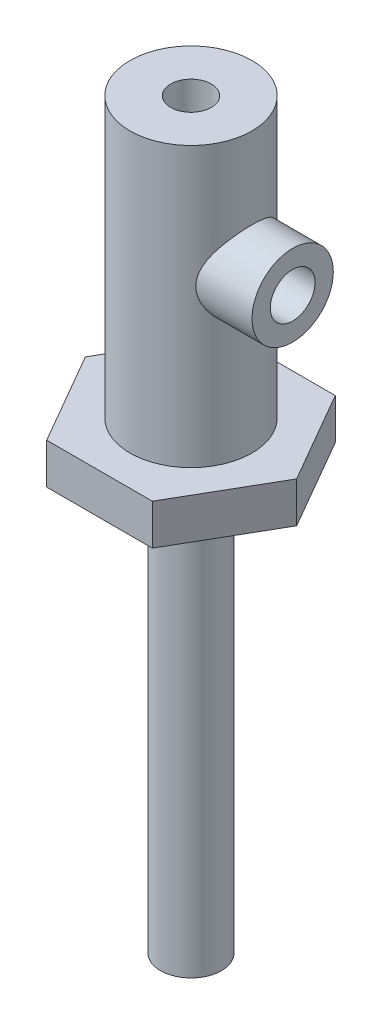
SolidWorks part; units mm, degrees
ref_plane "Front Plane" through (0, 0, 0) normal (0, 0, 1) x (1, 0, 0)
ref_plane "Top Plane" through (0, 0, 0) normal (0, 1, 0) x (1, 0, 0)
ref_plane "Right Plane" through (0, 0, 0) normal (1, 0, 0) x (0, 0, -1)
sketch "Sketch1" plane through (0, 0, 0) normal (0, 1, 0) x (1, 0, 0)
  circle A0 centre (0, 0) radius 3
  dimension "D1" = 6
extrude "Boss-Extrude1" add sketch "Sketch1" along normal blind 15.725
ref_plane "Plane1" through (0, 15.725, 0) normal (0, 1, 0) x (1, 0, 0)
ref_point "Point1"
sketch "Sketch2" plane through (0, 15.725, 0) normal (0, 1, 0) x (1, 0, 0)
  circle A0 centre (0, 0) radius 1
  dimension "D1" = 2
extrude "Cut-Extrude3" cut sketch "Sketch2" against normal blind 10.2
ref_plane "Plane2" through (0, 0, 0) normal (0, -1, 0) x (-1, 0, 0)
sketch "Sketch3" plane through (0, 0, 0) normal (0, -1, 0) x (-1, 0, 0)
  line L1 (5.1962, 0) -> (2.5981, 4.5)
  line L2 (2.5981, 4.5) -> (-2.5981, 4.5)
  line L3 (-2.5981, 4.5) -> (-5.1962, 0)
  line L4 (-5.1962, 0) -> (-2.5981, -4.5)
  line L5 (-2.5981, -4.5) -> (2.5981, -4.5)
  line L6 (2.5981, -4.5) -> (5.1962, 0)
  circle A0 centre (0, 0) radius 4.5 construction
extrude "Boss-Extrude2" add sketch "Sketch3" against normal blind 2
sketch "Sketch4" plane through (0, 0, 0) normal (0, -1, 0) x (-1, 0, 0)
  circle A0 centre (0, 0) radius 1.5
  dimension "D1" = 3
extrude "Boss-Extrude3" add sketch "Sketch4" along normal blind 20.8
ref_plane "Plane3" through (3, 0, 0) normal (1, 0, 0) x (0, 0, -1)
sketch "Sketch6" plane through (3, 0, 0) normal (1, 0, 0) x (0, 0, -1)
  line L0 (3.3, 15.725) -> (-3.3, 15.725) construction
  circle A0 centre (0, 9.725) radius 1.1
  circle A1 centre (0, 9.725) radius 2
  dimension "D2" = 2.2
  dimension "D3" = 4
  dimension "D1" = 6
extrude "Boss-Extrude4" add sketch "Sketch6" along normal blind 2 and the other way blind 1
ref_point "Point3"
sketch "Sketch7" plane through (3, 0, 0) normal (1, 0, 0) x (0, 0, -1)
  circle A0 centre (0, 9.725) radius 1.1
extrude "Cut-Extrude4" cut sketch "Sketch7" against normal blind 3
